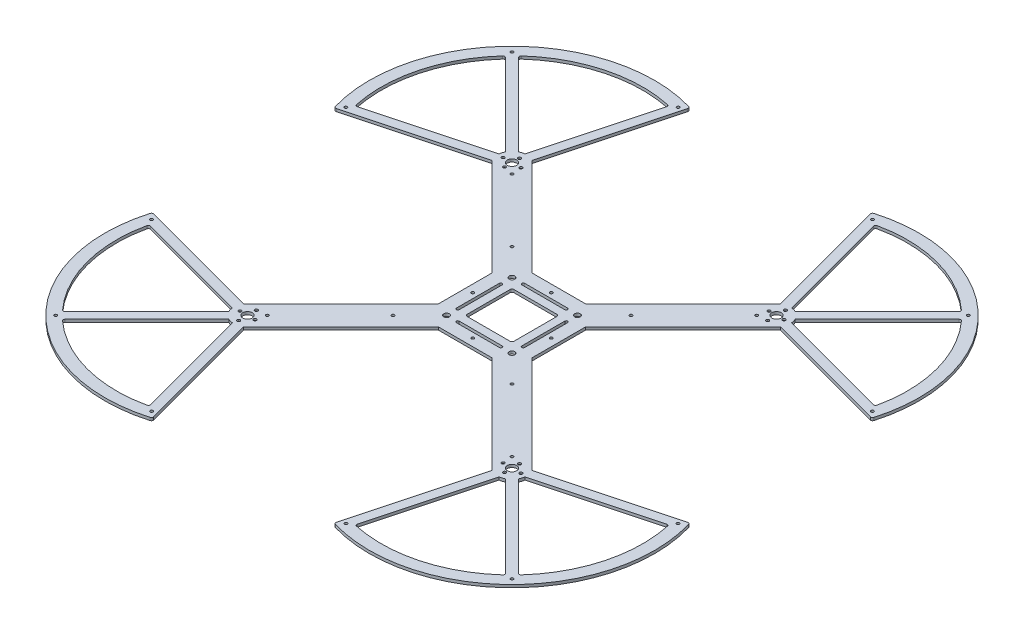
SolidWorks part; units mm, degrees
ref_plane "前视基准面" through (0, 0, 0) normal (0, 0, 1) x (1, 0, 0)
ref_plane "上视基准面" through (0, 0, 0) normal (0, 1, 0) x (1, 0, 0)
ref_plane "右视基准面" through (0, 0, 0) normal (1, 0, 0) x (0, 0, -1)
sketch "草图1" plane through (0, 0, 0) normal (0, 1, 0) x (1, 0, 0)
  line L0 (50, 28.7868) -> (154.0692, 132.856)
  line L1 (-28.7868, -50) -> (28.7868, -50)
  line L2 (-50, -28.7868) -> (-50, 28.7868)
  line L3 (-28.7868, 50) -> (28.7868, 50)
  line L4 (50, -28.7868) -> (50, 28.7868)
  line L5 (-40.8478, -40.8478) -> (50, 50) construction
  line L6 (-50, 50) -> (40.8478, -40.8478) construction
  line L7 (28.7868, 50) -> (132.856, 154.0692)
  line L8 (28.7868, 50) -> (50, 50) construction
  line L9 (50, 28.7868) -> (50, 50) construction
  line L10 (235.3409, 242.412) -> (147.8858, 154.9569)
  line L11 (242.412, 235.3409) -> (154.9569, 147.8858)
  line L12 (142.711, 146.2342) -> (13083.6632, 48442.5256) construction
  line L13 (97.6472, 285.4702) -> (132.856, 154.0692)
  line L14 (110.5799, 275.8416) -> (142.5907, 156.3757)
  line L15 (146.0703, 142.667) -> (48442.3616, 13083.6193) construction
  line L16 (275.8416, 110.5799) -> (156.3757, 142.5907)
  line L17 (285.4702, 97.6472) -> (154.0692, 132.856)
  line L18 (154.0692, 132.856) -> (152.028, 130.8148) construction
  line L19 (132.856, 154.0692) -> (130.8148, 152.028) construction
  line L20 (0, 0) -> (-50000, 0) construction
  line L21 (0, 0) -> (0, -50000) construction
  line L22 (-50, 28.7868) -> (-154.0692, 132.856)
  line L23 (-28.7868, 50) -> (-132.856, 154.0692)
  line L24 (-97.6472, 285.4702) -> (-132.856, 154.0692)
  line L25 (-285.4702, 97.6472) -> (-154.0692, 132.856)
  line L26 (-275.8416, 110.5799) -> (-156.3757, 142.5907)
  line L27 (-242.412, 235.3409) -> (-154.9569, 147.8858)
  line L28 (-235.3409, 242.412) -> (-147.8858, 154.9569)
  line L29 (-110.5799, 275.8416) -> (-142.5907, 156.3757)
  line L30 (-50, 50) -> (-28.7868, 50) construction
  line L31 (-50, 28.7868) -> (-50, 50) construction
  line L32 (50, -28.7868) -> (154.0692, -132.856)
  line L33 (28.7868, -50) -> (132.856, -154.0692)
  line L34 (-28.7868, -50) -> (-132.856, -154.0692)
  line L35 (-50, -28.7868) -> (-154.0692, -132.856)
  line L36 (97.6472, -285.4702) -> (132.856, -154.0692)
  line L37 (285.4702, -97.6472) -> (154.0692, -132.856)
  line L38 (-235.3409, -242.412) -> (-147.8858, -154.9569)
  line L39 (-110.5799, -275.8416) -> (-142.5907, -156.3757)
  line L40 (-242.412, -235.3409) -> (-154.9569, -147.8858)
  line L41 (-275.8416, -110.5799) -> (-156.3757, -142.5907)
  line L42 (-97.6472, -285.4702) -> (-132.856, -154.0692)
  line L43 (-285.4702, -97.6472) -> (-154.0692, -132.856)
  line L44 (275.8416, -110.5799) -> (156.3757, -142.5907)
  line L45 (242.412, -235.3409) -> (154.9569, -147.8858)
  line L46 (235.3409, -242.412) -> (147.8858, -154.9569)
  line L47 (110.5799, -275.8416) -> (142.5907, -156.3757)
  line L48 (-50, -50) -> (-50, -28.7868) construction
  line L49 (-50, -50) -> (-28.7868, -50) construction
  line L50 (28.7868, -50) -> (50, -50) construction
  line L51 (50, -50) -> (50, -28.7868) construction
  line L53 (-35, 35) -> (35, 35) construction
  line L54 (-35, 35) -> (-35, -35) construction
  line L55 (-35, -35) -> (35, -35) construction
  line L56 (35, 35) -> (35, -35) construction
  line L57 (-35, 35) -> (35, -35) construction
  line L58 (-35, -35) -> (35, 35) construction
  line L59 (-23, -25) -> (23, -25)
  line L60 (-25, -23) -> (-25, 23)
  line L61 (-23, 25) -> (23, 25)
  line L62 (25, -23) -> (25, 23)
  line L63 (-25, -25) -> (25, 25) construction
  line L64 (-25, 25) -> (25, -25) construction
  line L72 (33.5, 23) -> (33.5, -23)
  line L73 (36.5, -23) -> (36.5, 23)
  line L74 (-36.5, -23) -> (-36.5, 23)
  line L75 (-33.5, 23) -> (-33.5, -23)
  line L76 (23, 36.5) -> (-23, 36.5)
  line L77 (-23, 33.5) -> (23, 33.5)
  line L78 (-23, -33.5) -> (23, -33.5)
  line L79 (23, -36.5) -> (-23, -36.5)
  circle A0 centre (141.4214, 141.4214) radius 5
  arc A1 (156.3757, 142.5907) -> (154.9569, 147.8858) centre (141.4214, 141.4214) ccw
  arc A2 (42.4264, 42.4264) -> (50, 35.3924) centre (141.4214, 141.4214) ccw construction
  arc A3 (19.3624, 50) -> (33.5876, 33.5876) centre (141.4214, 141.4214) ccw construction
  arc A4 (32.3897, 53.6029) -> (35.3924, 50) centre (141.4214, 141.4214) ccw construction
  arc A5 (23.5039, 44.7171) -> (19.3624, 50) centre (141.4214, 141.4214) ccw construction
  arc A6 (50, 19.3624) -> (44.7171, 23.5039) centre (141.4214, 141.4214) ccw construction
  arc A7 (287.909, 99.023) -> (99.023, 287.909) centre (141.4214, 141.4214) ccw
  arc A8 (50, 35.3924) -> (53.6029, 32.3897) centre (141.4214, 141.4214) ccw construction
  arc A9 (278.3149, 112.0928) -> (245.3104, 235.2674) centre (141.4214, 141.4214) ccw
  arc A10 (33.5876, 33.5876) -> (50, 19.3624) centre (141.4214, 141.4214) ccw construction
  arc A11 (35.3924, 50) -> (42.4264, 42.4264) centre (141.4214, 141.4214) ccw construction
  arc A12 (53.6029, 32.3897) -> (105.1867, 6.1917) centre (141.4214, 141.4214) ccw construction
  arc A13 (44.7171, 23.5039) -> (101.9515, -5.8823) centre (141.4214, 141.4214) ccw construction
  arc A14 (6.1917, 105.1867) -> (32.3897, 53.6029) centre (141.4214, 141.4214) ccw construction
  arc A15 (-5.8823, 101.9515) -> (23.5039, 44.7171) centre (141.4214, 141.4214) ccw construction
  arc A16 (100.3802, 275.2706) -> (6.1917, 105.1867) centre (141.4214, 141.4214) ccw construction
  arc A17 (97.143, 287.3518) -> (-5.8823, 101.9515) centre (141.4214, 141.4214) ccw construction
  arc A18 (105.1867, 6.1917) -> (275.2706, 100.3802) centre (141.4214, 141.4214) ccw construction
  arc A19 (101.9515, -5.8823) -> (287.3518, 97.143) centre (141.4214, 141.4214) ccw construction
  arc A20 (152.028, 130.8148) -> (156.3757, 142.5907) centre (141.4214, 141.4214) ccw construction
  arc A21 (142.5907, 156.3757) -> (130.8148, 152.028) centre (141.4214, 141.4214) ccw construction
  arc A22 (152.028, 152.028) -> (147.8858, 154.9569) centre (141.4214, 141.4214) ccw construction
  arc A23 (147.8858, 154.9569) -> (142.5907, 156.3757) centre (141.4214, 141.4214) ccw
  arc A24 (154.9569, 147.8858) -> (152.028, 152.028) centre (141.4214, 141.4214) ccw construction
  arc A25 (110.0394, 277.8588) -> (100.3802, 275.2706) centre (141.4214, 141.4214) ccw construction
  arc A26 (240.4163, 240.4163) -> (236.8176, 243.8887) centre (141.4214, 141.4214) ccw construction
  arc A27 (235.2674, 245.3104) -> (112.0928, 278.3149) centre (141.4214, 141.4214) ccw
  arc A28 (243.8887, 236.8176) -> (240.4163, 240.4163) centre (141.4214, 141.4214) ccw construction
  arc A29 (275.2706, 100.3802) -> (277.8588, 110.0394) centre (141.4214, 141.4214) ccw construction
  arc A30 (-287.909, 99.023) -> (-99.023, 287.909) centre (-141.4214, 141.4214) cw
  arc A31 (-156.3757, 142.5907) -> (-154.9569, 147.8858) centre (-141.4214, 141.4214) cw
  arc A32 (-278.3149, 112.0928) -> (-245.3104, 235.2674) centre (-141.4214, 141.4214) cw
  arc A33 (-235.2674, 245.3104) -> (-112.0928, 278.3149) centre (-141.4214, 141.4214) cw
  arc A34 (-147.8858, 154.9569) -> (-142.5907, 156.3757) centre (-141.4214, 141.4214) cw
  circle A35 centre (-141.4214, 141.4214) radius 5
  circle A36 centre (141.4214, -141.4214) radius 5
  circle A37 centre (-141.4214, -141.4214) radius 5
  arc A38 (287.909, -99.023) -> (99.023, -287.909) centre (141.4214, -141.4214) cw
  arc A39 (-147.8858, -154.9569) -> (-142.5907, -156.3757) centre (-141.4214, -141.4214) ccw
  arc A40 (-235.2674, -245.3104) -> (-112.0928, -278.3149) centre (-141.4214, -141.4214) ccw
  arc A41 (-278.3149, -112.0928) -> (-245.3104, -235.2674) centre (-141.4214, -141.4214) ccw
  arc A42 (-156.3757, -142.5907) -> (-154.9569, -147.8858) centre (-141.4214, -141.4214) ccw
  arc A43 (-287.909, -99.023) -> (-99.023, -287.909) centre (-141.4214, -141.4214) ccw
  arc A44 (156.3757, -142.5907) -> (154.9569, -147.8858) centre (141.4214, -141.4214) cw
  arc A45 (278.3149, -112.0928) -> (245.3104, -235.2674) centre (141.4214, -141.4214) cw
  arc A46 (235.2674, -245.3104) -> (112.0928, -278.3149) centre (141.4214, -141.4214) cw
  arc A47 (147.8858, -154.9569) -> (142.5907, -156.3757) centre (141.4214, -141.4214) cw
  circle A49 centre (35, 35) radius 3
  circle A50 centre (35, -35) radius 3
  circle A51 centre (-35, -35) radius 3
  circle A52 centre (-35, 35) radius 3
  arc A55 (-25, 23) -> (-23, 25) centre (-23, 23) cw
  arc A56 (23, 25) -> (25, 23) centre (23, 23) cw
  arc A57 (23, -25) -> (25, -23) centre (23, -23) ccw
  arc A58 (-23, -25) -> (-25, -23) centre (-23, -23) cw
  arc A65 (285.4702, 97.6472) -> (287.909, 99.023) centre (285.9879, 99.5791) ccw
  arc A66 (275.8416, 110.5799) -> (278.3149, 112.0928) centre (276.3593, 112.5118) ccw
  arc A67 (235.3409, 242.412) -> (235.2674, 245.3104) centre (233.9267, 243.8262) ccw
  arc A68 (242.412, 235.3409) -> (245.3104, 235.2674) centre (243.8262, 233.9267) cw
  arc A69 (110.5799, 275.8416) -> (112.0928, 278.3149) centre (112.5118, 276.3593) cw
  arc A70 (97.6472, 285.4702) -> (99.023, 287.909) centre (99.5791, 285.9879) cw
  arc A71 (-287.909, 99.023) -> (-285.4702, 97.6472) centre (-285.9879, 99.5791) ccw
  arc A72 (-275.8416, 110.5799) -> (-278.3149, 112.0928) centre (-276.3593, 112.5118) cw
  arc A73 (-242.412, 235.3409) -> (-245.3104, 235.2674) centre (-243.8262, 233.9267) ccw
  arc A74 (-235.2674, 245.3104) -> (-235.3409, 242.412) centre (-233.9267, 243.8262) ccw
  arc A75 (-99.023, 287.909) -> (-97.6472, 285.4702) centre (-99.5791, 285.9879) cw
  arc A76 (-112.0928, 278.3149) -> (-110.5799, 275.8416) centre (-112.5118, 276.3593) cw
  arc A77 (285.4702, -97.6472) -> (287.909, -99.023) centre (285.9879, -99.5791) cw
  arc A78 (275.8416, -110.5799) -> (278.3149, -112.0928) centre (276.3593, -112.5118) cw
  arc A79 (242.412, -235.3409) -> (245.3104, -235.2674) centre (243.8262, -233.9267) ccw
  arc A80 (235.2674, -245.3104) -> (235.3409, -242.412) centre (233.9267, -243.8262) ccw
  arc A81 (112.0928, -278.3149) -> (110.5799, -275.8416) centre (112.5118, -276.3593) cw
  arc A82 (97.6472, -285.4702) -> (99.023, -287.909) centre (99.5791, -285.9879) ccw
  arc A83 (-285.4702, -97.6472) -> (-287.909, -99.023) centre (-285.9879, -99.5791) ccw
  arc A84 (-278.3149, -112.0928) -> (-275.8416, -110.5799) centre (-276.3593, -112.5118) cw
  arc A85 (-245.3104, -235.2674) -> (-242.412, -235.3409) centre (-243.8262, -233.9267) ccw
  arc A86 (-235.3409, -242.412) -> (-235.2674, -245.3104) centre (-233.9267, -243.8262) ccw
  arc A87 (-110.5799, -275.8416) -> (-112.0928, -278.3149) centre (-112.5118, -276.3593) cw
  arc A88 (-97.6472, -285.4702) -> (-99.023, -287.909) centre (-99.5791, -285.9879) cw
  arc A91 (36.5, 23) -> (33.5, 23) centre (35, 23) ccw
  arc A92 (33.5, -23) -> (36.5, -23) centre (35, -23) ccw
  arc A93 (33.5, 23) -> (35, 21.5) centre (35, 23) ccw construction
  arc A94 (35, 21.5) -> (36.5, 23) centre (35, 23) ccw construction
  arc A95 (35, -21.5) -> (33.5, -23) centre (35, -23) ccw construction
  arc A96 (36.5, -23) -> (35, -21.5) centre (35, -23) ccw construction
  arc A97 (-36.5, 23) -> (-33.5, 23) centre (-35, 23) cw
  arc A98 (-33.5, -23) -> (-36.5, -23) centre (-35, -23) cw
  arc A99 (23, 33.5) -> (23, 36.5) centre (23, 35) ccw
  arc A100 (-23, 36.5) -> (-23, 33.5) centre (-23, 35) ccw
  arc A101 (23, -33.5) -> (23, -36.5) centre (23, -35) cw
  arc A102 (-23, -36.5) -> (-23, -33.5) centre (-23, -35) cw
  circle A103 centre (243.9518, 243.9518) radius 1.5
  circle A104 centre (103.8926, 281.4806) radius 1.5
  circle A105 centre (281.4806, 103.8926) radius 1.5
  circle A106 centre (-103.8926, 281.4806) radius 1.5
  circle A107 centre (-281.4806, 103.8926) radius 1.5
  circle A108 centre (-243.9518, 243.9518) radius 1.5
  circle A109 centre (281.4806, -103.8926) radius 1.5
  circle A110 centre (243.9518, -243.9518) radius 1.5
  circle A111 centre (103.8926, -281.4806) radius 1.5
  circle A112 centre (-103.8926, -281.4806) radius 1.5
  circle A113 centre (-243.9518, -243.9518) radius 1.5
  circle A114 centre (-281.4806, -103.8926) radius 1.5
  circle A115 centre (42, 0) radius 1.5
  circle A116 centre (-42, 0) radius 1.5
  circle A117 centre (0, 42) radius 1.5
  circle A118 centre (0, -42) radius 1.5
  circle A119 centre (130.8148, 130.8148) radius 1.5
  circle A120 centre (63.6396, 63.6396) radius 1.5
  circle A121 centre (-63.6396, 63.6396) radius 1.5
  circle A122 centre (-130.8148, 130.8148) radius 1.5
  circle A123 centre (63.6396, -63.6396) radius 1.5
  circle A124 centre (130.8148, -130.8148) radius 1.5
  circle A125 centre (-130.8148, -130.8148) radius 1.5
  circle A126 centre (-63.6396, -63.6396) radius 1.5
  point P0 (0, 0)
  point P103 (-50, -50)
  point P104 (0, 0)
  point P112 (0, 0)
  point P163 (-287.3518, 97.143)
  point P166 (-277.8588, 110.0394)
  point P169 (-243.8887, 236.8176)
  point P172 (-236.8176, 243.8887)
  point P175 (-97.143, 287.3518)
  point P178 (-110.0394, 277.8588)
  point P181 (287.3518, -97.143)
  point P184 (277.8588, -110.0394)
  point P187 (243.8887, -236.8176)
  point P190 (236.8176, -243.8887)
  point P193 (110.0394, -277.8588)
  point P196 (97.143, -287.3518)
  point P199 (-287.3518, -97.143)
  point P202 (-277.8588, -110.0394)
  point P205 (-243.8887, -236.8176)
  point P208 (-236.8176, -243.8887)
  point P211 (-110.0394, -277.8588)
  point P214 (-97.143, -287.3518)
  dimension "D5" = 10
  dimension "D7" = 30
  dimension "D8" = 280
  dimension "D11" = 305
  dimension "D15" = 6
  dimension "D16" = 6
  dimension "D17" = 6
  dimension "D18" = 6
  dimension "D20" = 2
  dimension "D23" = 2
  dimension "D24" = 2
  dimension "D25" = 12
  dimension "D21" = 3
  dimension "D22" = 3
  dimension "D27" = 3
  dimension "D29" = 3
  dimension "D31" = 3
  dimension "D33" = 3
  dimension "D1" = 100
  dimension "D2" = 100
  dimension "D3" = 15
  dimension "D4" = 15
  dimension "D6" = 200
  dimension "D9" = 5
  dimension "D10" = 30
  dimension "D12" = 10
  dimension "D13" = 10
  dimension "D14" = 70
  dimension "D19" = 50
  dimension "D26" = 12
  dimension "D28" = 145
  dimension "D30" = 8
  dimension "D32" = 15
  dimension "D34" = 110
extrude "凸台-拉伸1" add sketch "草图1" along normal blind 3
sketch "草图4" plane through (0, 0, 0) normal (0, -1, 0) x (1, 0, 0)
  line L0 (0, 0) -> (-35355.3391, 35355.3391) construction
  line L1 (0, 0) -> (50000, 0) construction
  line L2 (131.9214, -141.4214) -> (141.4214, -150.9214) construction
  line L3 (131.9214, -141.4214) -> (141.4214, -131.9214) construction
  line L4 (141.4214, -131.9214) -> (150.9214, -141.4214) construction
  line L5 (141.4214, -150.9214) -> (150.9214, -141.4214) construction
  line L6 (131.9214, -141.4214) -> (150.9214, -141.4214) construction
  line L7 (141.4214, -131.9214) -> (141.4214, -150.9214) construction
  line L8 (141.4214, -133.4214) -> (133.4214, -141.4214) construction
  line L9 (141.4214, -133.4214) -> (149.4214, -141.4214) construction
  line L10 (149.4214, -141.4214) -> (141.4214, -149.4214) construction
  line L11 (133.4214, -141.4214) -> (141.4214, -149.4214) construction
  line L12 (141.4214, -133.4214) -> (141.4214, -149.4214) construction
  line L13 (149.4214, -141.4214) -> (133.4214, -141.4214) construction
  line L14 (0, 0) -> (0, 108.7601) construction
  line L15 (-149.4214, -141.4214) -> (-133.4214, -141.4214) construction
  line L16 (-141.4214, -133.4214) -> (-141.4214, -149.4214) construction
  line L17 (-133.4214, -141.4214) -> (-141.4214, -149.4214) construction
  line L18 (-149.4214, -141.4214) -> (-141.4214, -149.4214) construction
  line L19 (-141.4214, -133.4214) -> (-149.4214, -141.4214) construction
  line L20 (-141.4214, -133.4214) -> (-133.4214, -141.4214) construction
  line L21 (-141.4214, -131.9214) -> (-141.4214, -150.9214) construction
  line L22 (-131.9214, -141.4214) -> (-150.9214, -141.4214) construction
  line L23 (-141.4214, -150.9214) -> (-150.9214, -141.4214) construction
  line L24 (-141.4214, -131.9214) -> (-150.9214, -141.4214) construction
  line L25 (-131.9214, -141.4214) -> (-141.4214, -131.9214) construction
  line L26 (-131.9214, -141.4214) -> (-141.4214, -150.9214) construction
  line L27 (149.4214, 141.4214) -> (133.4214, 141.4214) construction
  line L28 (141.4214, 133.4214) -> (141.4214, 149.4214) construction
  line L29 (133.4214, 141.4214) -> (141.4214, 149.4214) construction
  line L30 (149.4214, 141.4214) -> (141.4214, 149.4214) construction
  line L31 (141.4214, 133.4214) -> (149.4214, 141.4214) construction
  line L32 (141.4214, 133.4214) -> (133.4214, 141.4214) construction
  line L33 (141.4214, 131.9214) -> (141.4214, 150.9214) construction
  line L34 (131.9214, 141.4214) -> (150.9214, 141.4214) construction
  line L35 (141.4214, 150.9214) -> (150.9214, 141.4214) construction
  line L36 (141.4214, 131.9214) -> (150.9214, 141.4214) construction
  line L37 (131.9214, 141.4214) -> (141.4214, 131.9214) construction
  line L38 (131.9214, 141.4214) -> (141.4214, 150.9214) construction
  line L39 (-131.9214, 141.4214) -> (-141.4214, 150.9214) construction
  line L40 (-131.9214, 141.4214) -> (-141.4214, 131.9214) construction
  line L41 (-141.4214, 131.9214) -> (-150.9214, 141.4214) construction
  line L42 (-141.4214, 150.9214) -> (-150.9214, 141.4214) construction
  line L43 (-131.9214, 141.4214) -> (-150.9214, 141.4214) construction
  line L44 (-141.4214, 131.9214) -> (-141.4214, 150.9214) construction
  line L45 (-141.4214, 133.4214) -> (-133.4214, 141.4214) construction
  line L46 (-141.4214, 133.4214) -> (-149.4214, 141.4214) construction
  line L47 (-149.4214, 141.4214) -> (-141.4214, 149.4214) construction
  line L48 (-133.4214, 141.4214) -> (-141.4214, 149.4214) construction
  line L49 (-141.4214, 133.4214) -> (-141.4214, 149.4214) construction
  line L50 (-149.4214, 141.4214) -> (-133.4214, 141.4214) construction
  point P4 (141.4214, -141.4214)
  point P9 (141.4214, -141.4214)
  point P26 (-141.4214, -141.4214)
  point P35 (141.4214, 141.4214)
  point P44 (-141.4214, 141.4214)
  dimension "D1" = 19
  dimension "D2" = 90
  dimension "D3" = 90
  dimension "D4" = 16
  dimension "D5" = 45
hole_wizard "大小十字凹头螺钉锥孔1" positions "3D草图2" profile "草图7" countersink size "M3" standard "AS" end condition through all
sketch3d "3D草图2"
  point P0 (141.4214, 0, -131.9214)
  point P3 (149.4214, 0, -141.4214)
  point P6 (141.4214, 0, -150.9214)
  point P9 (133.4214, 0, -141.4214)
  point P12 (131.9214, 0, 141.4214)
  point P15 (150.9214, 0, 141.4214)
  point P18 (141.4214, 0, 133.4214)
  point P21 (141.4214, 0, 149.4214)
  point P24 (-141.4214, 0, 131.9214)
  point P27 (-141.4214, 0, 150.9214)
  point P30 (-133.4214, 0, 141.4214)
  point P33 (-149.4214, 0, 141.4214)
  point P36 (-131.9214, 0, -141.4214)
  point P39 (-150.9214, 0, -141.4214)
  point P42 (-141.4214, 0, -149.4214)
  point P45 (-141.4214, 0, -133.4214)
sketch "草图7" plane through (141.4214, 0, -131.9214) normal (1, 0, 0) x (0, 0, -1)
  line L0 (0, 0) -> (0, 3)
  line L1 (0, 3) -> (1.6, 3)
  line L2 (1.6, 3) -> (1.6, 1.25)
  line L3 (1.6, 1.25) -> (2.85, 0)
  line L5 (2.85, 0) -> (0, 0)
  line L6 (-1.6, 1.25) -> (-2.85, 0) construction
  line L11 (0, -6.35) -> (0, 107.95) construction
  dimension "通孔孔直径" = 3.2
  dimension "通孔孔深度" = 3
  dimension "近端锥形沉头孔直径" = 5.7
  dimension "近端锥形沉头孔角度" = 90
